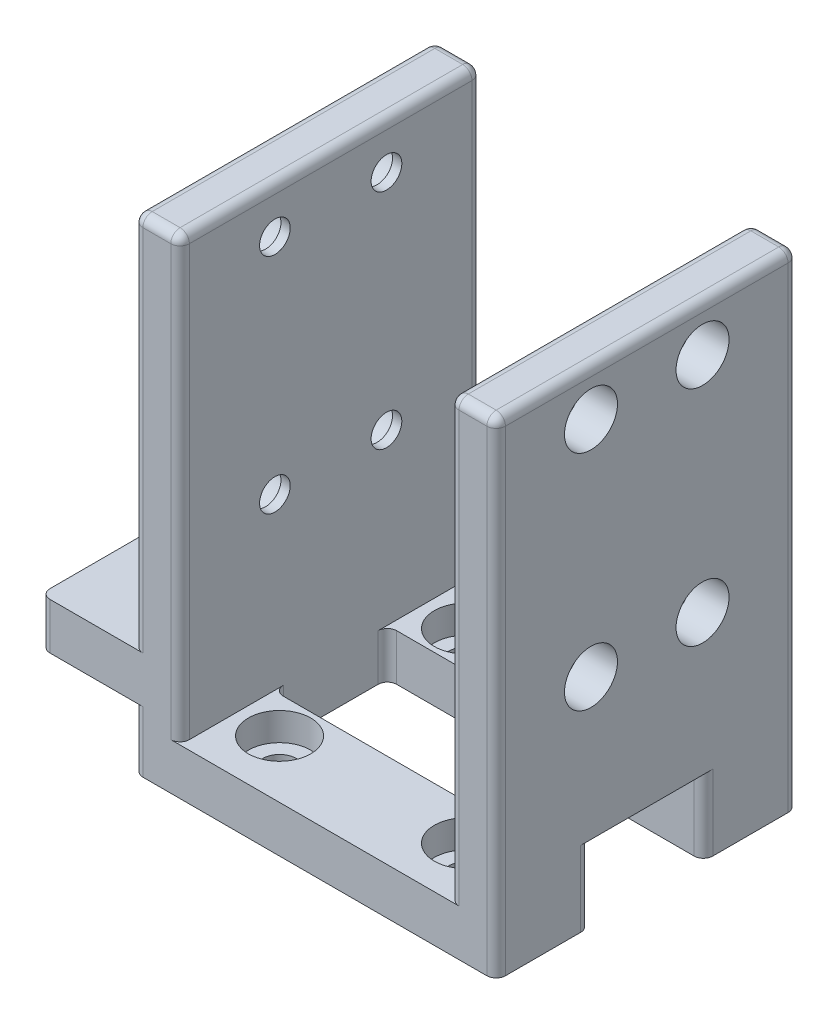
SolidWorks part; units mm, degrees
material "ABS"
ref_plane "Front Plane" through (0, 0, 0) normal (0, 0, 1) x (1, 0, 0)
ref_plane "Top Plane" through (0, 0, 0) normal (0, 1, 0) x (1, 0, 0)
ref_plane "Right Plane" through (0, 0, 0) normal (1, 0, 0) x (0, 0, -1)
sketch "Sketch1" plane through (0, 0, 0) normal (0, 0, 1) x (1, 0, 0)
  line L0 (0, 0) -> (0, 47.2)
  line L1 (0, 47.2) -> (-5, 47.2)
  line L2 (-5, 47.2) -> (-5, -5)
  line L3 (-5, -5) -> (34, -5)
  line L4 (34, -5) -> (34, 47.2)
  line L5 (34, 47.2) -> (29, 47.2)
  line L6 (29, 47.2) -> (29, 0)
  line L7 (29, 0) -> (0, 0)
  dimension "D1" = 5
  dimension "D2" = 5
  dimension "D3" = 5
  dimension "D4" = 39
  dimension "D5" = 52.2
extrude "Boss-Extrude1" add sketch "Sketch1" along normal up to surface (32.4 mm away)
sketch "Sketch2" plane through (34, 0, 0) normal (1, 0, 0) x (0, 0, -1)
  line L0 (-32.4, -5) -> (0, -5) construction
  line L1 (-22.3, -5) -> (-10.1, -5)
  line L2 (-22.3, -5) -> (-22.3, 3.1)
  line L3 (-22.3, 3.1) -> (-10.1, 3.1)
  line L4 (-10.1, -5) -> (-10.1, 3.1)
  point P6 (-16.2, -5)
  point P7 (-16.2, -5)
  dimension "D1" = 0
  dimension "D2" = 12.2
  dimension "D3" = 8.1
extrude "Cut-Extrude1" cut sketch "Sketch2" against normal up to surface (34 mm away) up to face at (0, 23.6, 16.2)
hole_wizard "CBORE for M3 SHCS1" positions "Sketch3" profile "Sketch4" counterbore size "M3" standard "ANSI Metric" end condition through all
sketch "Sketch3" plane through (0, 0, 0) normal (0, 1, 0) x (1, 0, 0)
  line L2 (29, 0) -> (0, 0) construction
  line L3 (0, -22.3) -> (0, -10.1) construction
  point P0 (4.5, -26.2)
  point P2 (24.5, -26.2)
  point P4 (4.5, -6.2)
  point P6 (24.5, -6.2)
  point P24 (14.5, 0)
  point P27 (0, -16.2)
  dimension "D1" = 10
  dimension "D2" = 10
  dimension "D3" = 10
  dimension "D4" = 10
sketch "Sketch4" plane through (4.5, 0, 26.2) normal (1, 0, 0) x (0, 0, 1)
  line L0 (0, 0) -> (0, 5)
  line L1 (0, 5) -> (1.8, 5)
  line L3 (1.8, 5) -> (1.8, 3)
  line L4 (1.8, 3) -> (3.35, 3)
  line L5 (3.35, 3) -> (3.35, 0)
  line L7 (3.35, 0) -> (0, 0)
  line L11 (0, -6.35) -> (0, 107.95) construction
  dimension "Thru Hole Dia." = 3.6
  dimension "Thru Hole Depth" = 5
  dimension "C'Bore Dia." = 6.7
  dimension "C'Bore Depth" = 3
hole_wizard "CBORE for M2.5 SHCS1" positions "Sketch5" profile "Sketch6" counterbore size "M2.5" standard "ANSI Metric"
sketch "Sketch5" plane through (-5, 0, 0) normal (-1, 0, 0) x (0, 0, 1)
  point P0 (10.2, 42.25)
  point P2 (22.2, 42.25)
  point P4 (10.2, 18.25)
  point P6 (22.2, 18.25)
sketch "Sketch6" plane through (-5, 42.25, 10.2) normal (0, 1, 0) x (0, 0, 1)
  line L0 (0, 0) -> (0, 39)
  line L1 (0, 39) -> (1.65, 39)
  line L3 (1.65, 39) -> (1.65, 4)
  line L4 (1.65, 4) -> (2.85, 4)
  line L5 (2.85, 4) -> (2.85, 0)
  line L7 (2.85, 0) -> (0, 0)
  line L11 (0, -6.35) -> (0, 107.95) construction
  dimension "Thru Hole Dia." = 3.3
  dimension "Thru Hole Depth" = 39
  dimension "C'Bore Dia." = 5.7
  dimension "C'Bore Depth" = 4
ref_plane "Plane1" through (14.5, 0, 0) normal (-1, 0, 0) x (0, 0, 1)
mirror "Mirror1" about plane through (14.5, 0, 0) normal (-1, 0, 0) of "CBORE for M2.5 SHCS1"
sketch "Sketch7" plane through (-5, 0, 0) normal (-1, 0, 0) x (0, 0, 1)
  line L0 (0, 47.2) -> (0, -5) construction
  line L1 (0, 1.569) -> (13.7, 1.569)
  line L2 (0, 1.569) -> (0, 6.569)
  line L3 (0, 6.569) -> (13.7, 6.569)
  line L4 (13.7, 1.569) -> (13.7, 6.569)
  line L5 (32.4, -5) -> (32.4, 47.2) construction
  line L6 (32.4, 1.569) -> (18.7, 1.569)
  line L7 (32.4, 1.569) -> (32.4, 6.569)
  line L8 (32.4, 6.569) -> (18.7, 6.569)
  line L9 (18.7, 1.569) -> (18.7, 6.569)
  line L10 (32.4, -5) -> (0, -5) construction
  dimension "D1" = 5
  dimension "D2" = 5
  dimension "D3" = 6.569
extrude "Boss-Extrude2" add sketch "Sketch7" along normal up to surface (10 mm away)
fillet "Fillet1" radius 1 29 edges at (31.5, 47.2, 0) (34, 47.2, 16.2) (31.5, 47.2, 32.4) (29, 47.2, 16.2) (34, -0.95, 10.1) (34, -0.95, 22.3) (0, -2.5, 22.3) (0, -2.5, 10.1) (0, 23.6, 32.4) (-5, 26.8845, 32.4) (-2.5, 47.2, 32.4) (0, 47.2, 16.2) (-2.5, 47.2, 0) (-5, 26.8845, 0) (-5, 47.2, 16.2) (-5, 4.069, 18.7) (-5, 4.069, 13.7) (-15, 4.069, 13.7) (-15, 4.069, 0) (-15, 4.069, 18.7) (-15, 4.069, 32.4) (0, 23.6, 0) (14.5, 0, 0) (29, 23.6, 0) (34, 21.1, 0) (29, 23.6, 32.4) (34, 21.1, 32.4) (-5, -1.7155, 32.4) (-5, -1.7155, 0)
